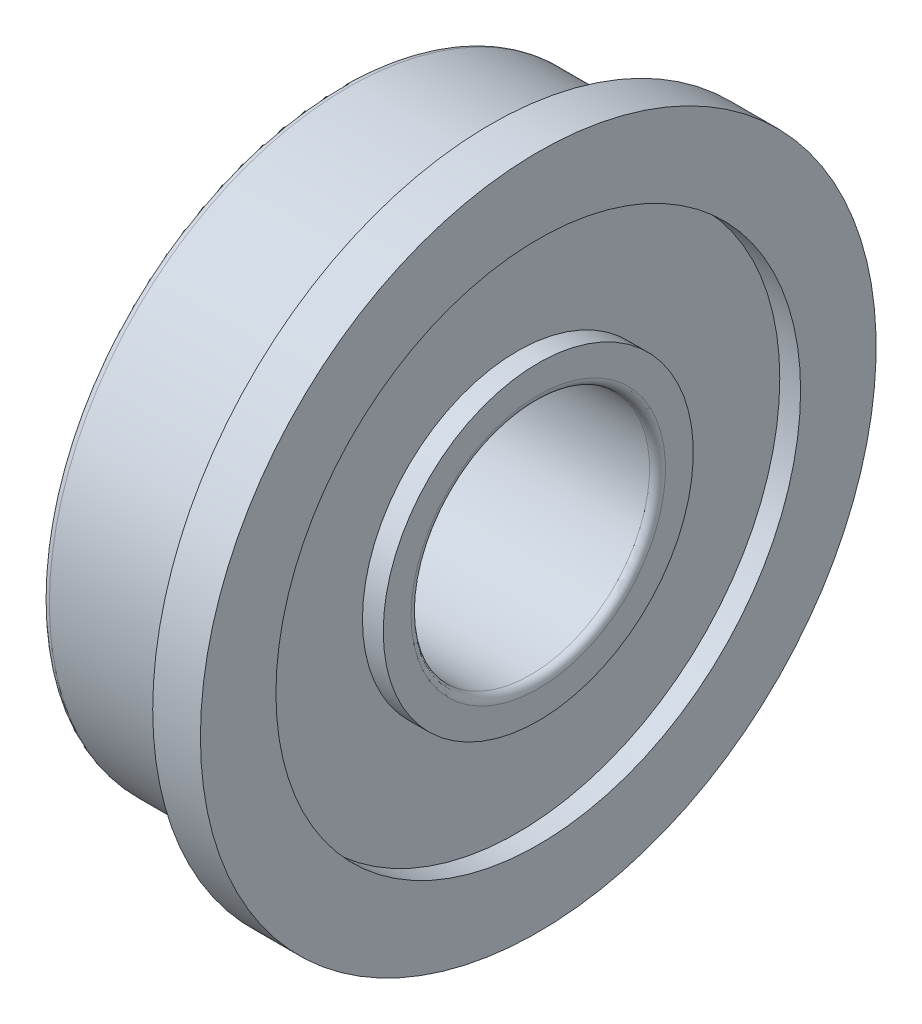
SolidWorks part; units mm, degrees
ref_plane "Front Plane" through (0, 0, 0) normal (0, 0, 1) x (1, 0, 0)
ref_plane "Top Plane" through (0, 0, 0) normal (0, 1, 0) x (1, 0, 0)
ref_plane "Right Plane" through (0, 0, 0) normal (1, 0, 0) x (0, 0, -1)
ref_plane "Plane1" through (0, 0, 0) normal (0, 0, 1) x (1, 0, 0)
sketch "Sketch1" plane through (0, 0, 0) normal (0, 0, 1) x (1, 0, 0)
  line L0 (0, 7.3) -> (0, 6.6)
  line L1 (0, 6.6) -> (0.5238, 6.6)
  line L2 (0.5238, 6.6) -> (0.5238, 3.9)
  line L3 (0.5238, 3.9) -> (0, 3.9)
  line L4 (0, 3.9) -> (0, 3.2)
  line L5 (0.2, 3) -> (4.8, 3)
  line L6 (5, 3.2) -> (5, 3.9)
  line L7 (5, 3.9) -> (4.4763, 3.9)
  line L8 (4.4763, 3.9) -> (4.4763, 6.6)
  line L9 (4.4763, 6.6) -> (5, 6.6)
  line L10 (5, 6.6) -> (5, 8.5)
  line L11 (5, 8.5) -> (3.8, 8.5)
  line L12 (3.8, 8.5) -> (3.8, 7.7)
  line L13 (3.6, 7.5) -> (0.2, 7.5)
  line L14 (15, 0) -> (-15, 0) construction
  arc A0 (0, 3.2) -> (0.2, 3) centre (0.2, 3.2) ccw
  arc A1 (4.8, 3) -> (5, 3.2) centre (4.8, 3.2) ccw
  arc A2 (3.8, 7.7) -> (3.6, 7.5) centre (3.8, 7.5) cw
  arc A3 (0.2, 7.5) -> (0, 7.3) centre (0.2, 7.3) ccw
revolve "Revolve1" add sketch "Sketch1" angle 360 about L14
